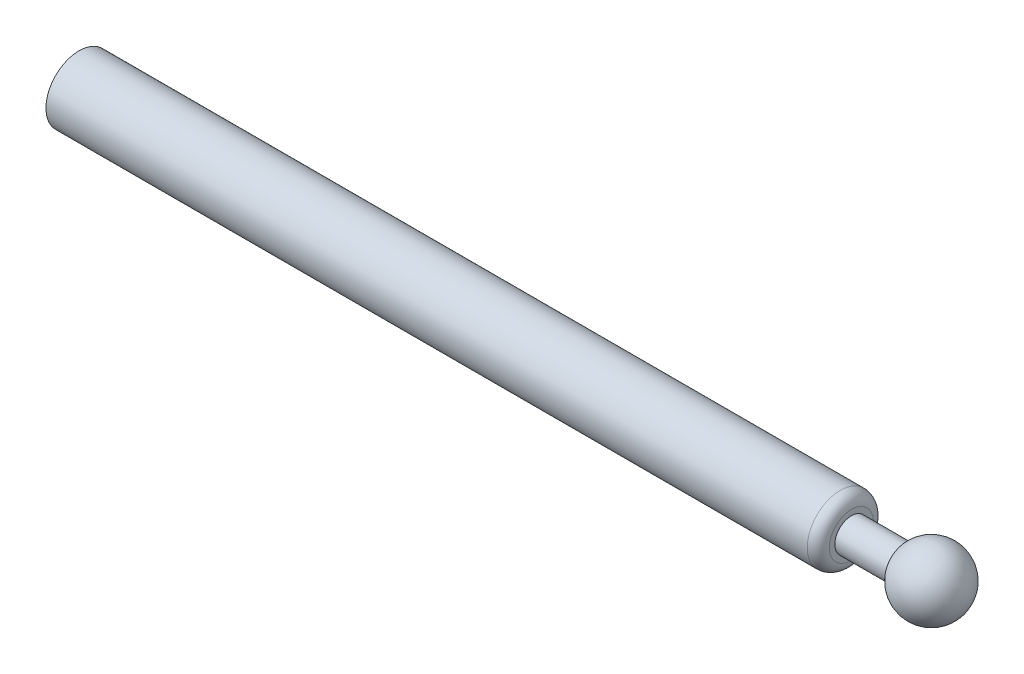
SolidWorks part; units mm, degrees
ref_plane "Front Plane" through (0, 0, 0) normal (0, 0, 1) x (1, 0, 0)
ref_plane "Top Plane" through (0, 0, 0) normal (0, 1, 0) x (1, 0, 0)
ref_plane "Right Plane" through (0, 0, 0) normal (1, 0, 0) x (0, 0, -1)
sketch "Sketch2" plane through (0, 0, 0) normal (1, 0, 0) x (0, 0, -1)
  circle A0 centre (0, 0) radius 3
extrude "Boss-Extrude1" add sketch "Sketch2" along normal blind 70
sketch "Sketch3" plane through (70, 0, 0) normal (1, 0, 0) x (0, 0, -1)
  circle A0 centre (0, 0) radius 1.5
extrude "Boss-Extrude2" add sketch "Sketch3" along normal blind 5
fillet "Fillet1" radius 1 1 edges at (70, 0, -3)
sketch "Sketch4" plane through (0, 0, 0) normal (0, 0, 1) x (1, 0, 0)
  line L0 (75, 0) -> (77.25, 0)
  line L1 (75, -1.5) -> (75, 1.5) construction
  line L2 (77.25, 0) -> (80.25, 0)
  line L3 (75, 0) -> (74.25, 0)
  arc A0 (74.25, 0) -> (80.25, 0) centre (77.25, 0) ccw
  dimension "D2" = 6
  dimension "D1" = 2.25
revolve "Revolve1" add sketch "Sketch4" angle 360 about L0
